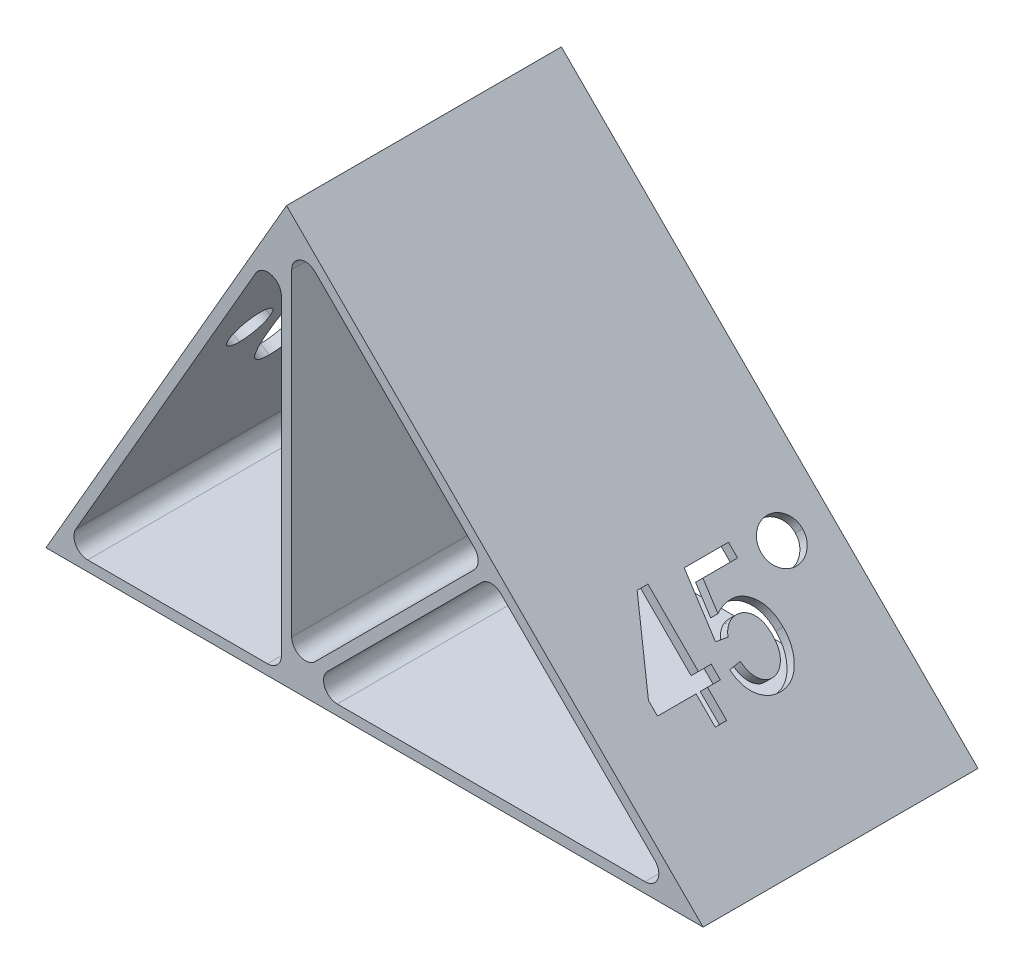
SolidWorks part; units mm, degrees
ref_plane "Plan de face" through (0, 0, 0) normal (0, 0, 1) x (1, 0, 0)
ref_plane "Plan de dessus" through (0, 0, 0) normal (0, 1, 0) x (1, 0, 0)
ref_plane "Plan de droite" through (0, 0, 0) normal (1, 0, 0) x (0, 0, -1)
sketch "Esquisse1" plane through (0, 0, 0) normal (0, 0, 1) x (1, 0, 0)
  line L0 (-17.5, 0) -> (0, 30.3109)
  line L1 (0, 30.3109) -> (30.3109, 0)
  line L2 (30.3109, 0) -> (-17.5, 0)
  line L3 (-16.201, 0.75) -> (-0.375, 28.1614)
  line L4 (0.375, 28.8752) -> (14.3599, 14.8903)
  line L5 (28.5002, 0.75) -> (1.2803, 0.75)
  line L6 (0, 0) -> (0, 45.3247) construction
  line L7 (-0.375, 28.1614) -> (-0.375, 0.75)
  line L8 (0.375, 28.8752) -> (0.375, 0.9053)
  line L9 (-0.375, 0.75) -> (-16.201, 0.75)
  line L10 (0.1608, 29.0894) -> (28.5002, 0.75) construction
  line L11 (-16.201, 0.75) -> (0.1608, 29.0894) construction
  line L12 (0, 0) -> (14.6251, 14.6251) construction
  line L13 (28.5002, 0.75) -> (-16.201, 0.75) construction
  line L14 (14.3599, 14.8903) -> (0.375, 0.9053)
  line L15 (14.8903, 14.3599) -> (1.2803, 0.75)
  line L16 (14.8903, 14.3599) -> (28.5002, 0.75)
  point P18 (0.5, 1.2241)
  dimension "D1" = 35
  dimension "D2" = 45
  dimension "D3" = 60
  dimension "D5" = 0.75
  dimension "D6" = 0.75
  dimension "D4" = 0.75
extrude "Boss.-Extru.1" add sketch "Esquisse1" along normal mid plane 20
sketch "Esquisse2" plane through (15.1554, 15.1554, 0) normal (0.7071, 0.7071, 0) x (0, 0, -1)
  text T0 "45°" font "Arial Narrow" height 8
extrude "Enlèv. mat.-Extru.1" cut sketch "Esquisse2" against normal up to next
sketch "Esquisse3" plane through (15.1554, 15.1554, 0) normal (0.7071, 0.7071, 0) x (0, 0, -1)
  line L3 (-3.0355, -9.9244) -> (-3.0355, -6.3092)
  line L4 (-3.0355, -6.3092) -> (-5.0209, -9.9244)
  line L5 (-5.0209, -9.9244) -> (-3.0355, -9.9244)
  line L6 (-3.0355, -9.9244) -> (-3.0355, -6.3092)
  line L7 (-3.0355, -6.3092) -> (-5.0209, -9.9244)
  line L8 (-5.0209, -9.9244) -> (-3.0355, -9.9244)
  spline S4 degree 3 poles (-2963.6415, -433.431) (43.6454, 7.477) (4.5204, -2.4903) (5.7443, -6.5374) (5.8165, -6.6726) (5.9173, -6.791) (6.0366, -6.8905) (6.1713, -6.9629) (10.2236, -8.1858) (20.1312, 30.9085) (-416.3585, -2976.9328) knots -9.881018 -9.881018 -9.881018 -9.881018 0.127723 0.249273 0.372542 0.500423 0.627458 0.750727 0.872277 10.890294 10.890294 10.890294 10.890294 only from (5.6918, -6.2361) to (6.4726, -7.0153)
  spline S5 degree 3 poles (417.2761, -2978.638) (-6.9739, 30.4862) (2.7124, -8.1772) (6.7721, -6.9633) (6.9057, -6.89) (7.0247, -6.7911) (7.1255, -6.6726) (7.1977, -6.5374) (8.4216, -2.49) (-30.7024, 7.4708) (2976.6162, -432.9519) knots -9.923353 -9.923353 -9.923353 -9.923353 0.126719 0.248571 0.37098 0.49833 0.62653 0.750107 0.871959 10.905972 10.905972 10.905972 10.905972 only from (6.4726, -7.0153) to (7.2502, -6.2361)
  spline S6 degree 3 poles (2978.071, 410.2359) (-30.5756, -19.819) (8.4175, -10.0006) (7.1981, -5.9351) (7.125, -5.8009) (7.0243, -5.6829) (6.9062, -5.5821) (6.772, -5.509) (2.7195, -4.2937) (-7.0566, -42.9957) (423.9488, 2965.2214) knots -9.945525 -9.945525 -9.945525 -9.945525 0.128082 0.249973 0.372421 0.500661 0.628902 0.751349 0.87324 10.914077 10.914077 10.914077 10.914077 only from (7.2502, -6.2361) to (6.4726, -5.4569)
  spline S7 degree 3 poles (-422.8526, 2963.5136) (20.2129, -43.4174) (10.2166, -4.2852) (6.1714, -5.5095) (6.0361, -5.5816) (5.9178, -5.6829) (5.817, -5.8009) (5.744, -5.9351) (4.5245, -10.0003) (43.5189, -19.8252) (-2965.1311, 410.7236) knots -9.881265 -9.881265 -9.881265 -9.881265 0.127764 0.249352 0.372661 0.500583 0.628505 0.750648 0.872236 10.920502 10.920502 10.920502 10.920502 only from (6.4726, -5.4569) to (5.6918, -6.2361)
  spline S8 degree 3 poles (5.6918, -6.2361) (5.6945, -6.2884) (5.6999, -6.3904) (5.7443, -6.5374) (5.8165, -6.6726) (5.9173, -6.791) (6.0366, -6.8905) (6.1713, -6.9629) (6.3184, -7.0073) (6.4204, -7.0126) (6.4726, -7.0153) knots 0 0 0 0 0.127723 0.249273 0.372542 0.500423 0.627458 0.750727 0.872277 1 1 1 1
  spline S9 degree 3 poles (6.4726, -7.0153) (6.5244, -7.0125) (6.6258, -7.007) (6.7721, -6.9633) (6.9057, -6.89) (7.0247, -6.7911) (7.1255, -6.6726) (7.1977, -6.5374) (7.2422, -6.3904) (7.2475, -6.2884) (7.2502, -6.2361) knots 0 0 0 0 0.126719 0.248571 0.37098 0.49833 0.62653 0.750107 0.871959 1 1 1 1
  spline S10 degree 3 poles (7.2502, -6.2361) (7.2475, -6.1839) (7.2421, -6.0819) (7.1981, -5.9351) (7.125, -5.8009) (7.0243, -5.6829) (6.9062, -5.5821) (6.772, -5.509) (6.6258, -5.4652) (6.5244, -5.4597) (6.4726, -5.4569) knots 0 0 0 0 0.128082 0.249973 0.372421 0.500661 0.628902 0.751349 0.87324 1 1 1 1
  spline S11 degree 3 poles (6.4726, -5.4569) (6.4204, -5.4596) (6.3184, -5.465) (6.1714, -5.5095) (6.0361, -5.5816) (5.9178, -5.6829) (5.817, -5.8009) (5.744, -5.9351) (5.6999, -6.0819) (5.6946, -6.1839) (5.6918, -6.2361) knots 0 0 0 0 0.127764 0.249352 0.372661 0.500583 0.628505 0.750648 0.872236 1 1 1 1
  dimension "D1" = 0
  dimension "D2" = 0
extrude "Enlèv. mat.-Extru.2" cut sketch "Esquisse3" against normal up to next (0.75 mm away)
sketch "Esquisse4" plane through (-13.125, 7.5777, 0) normal (-0.866, 0.5, 0) x (0, 0, 1)
  text T0 "60°" font "Arial Narrow" height 8
extrude "Enlèv. mat.-Extru.3" cut sketch "Esquisse4" against normal up to next
fillet "Congé1" radius 1 9 edges at (14.8903, 14.3599, 0) (0.375, 28.8752, 0) (-0.375, 28.1614, 0) (14.3599, 14.8903, 0) (28.5002, 0.75, 0) (-16.201, 0.75, 0) (1.2803, 0.75, 0) (0.375, 0.9053, 0) (-0.375, 0.75, 0)
